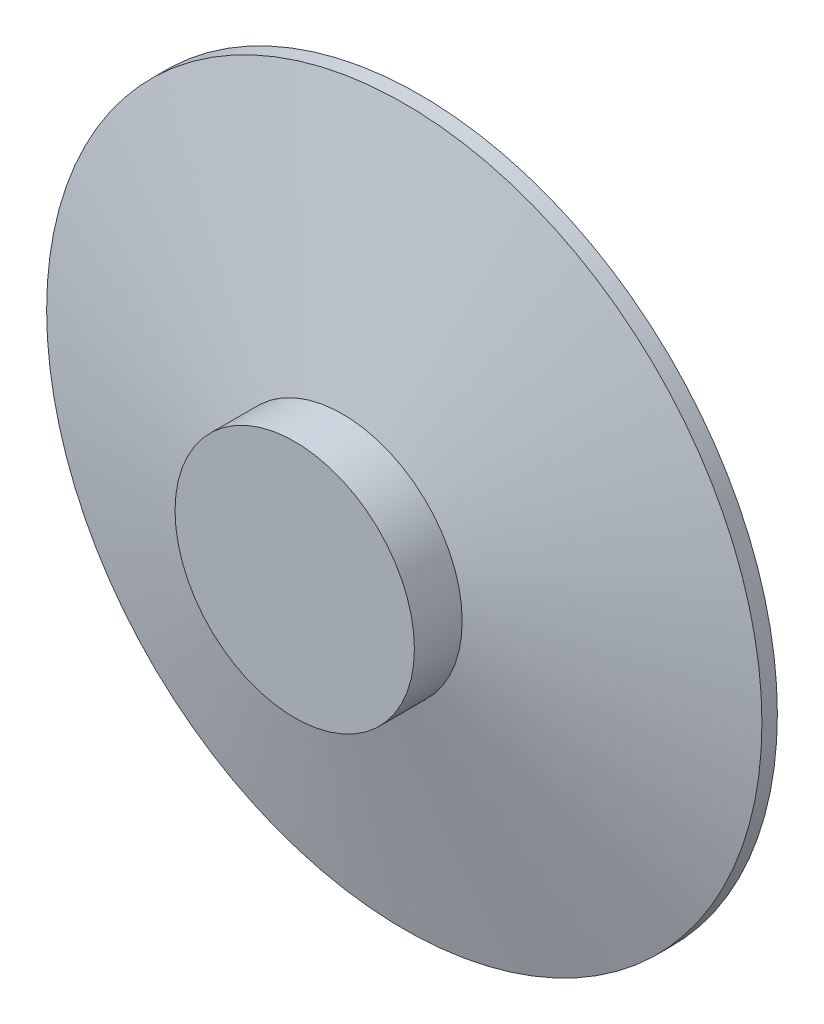
SolidWorks part; units mm, degrees
material "6061-T6 (SS)"
ref_plane "Front" through (0, 0, 0) normal (0, 0, 1) x (1, 0, 0)
ref_plane "Top" through (0, 0, 0) normal (0, 1, 0) x (1, 0, 0)
ref_plane "Right" through (0, 0, 0) normal (1, 0, 0) x (0, 0, -1)
sketch "Sketch1" plane through (0, 0, 0) normal (1, 0, 0) x (0, 0, -1)
  line L0 (0, 0) -> (47.2597, 0) construction
  line L1 (0, 0) -> (0, 5.8274)
  line L2 (0, 5.8274) -> (2.327, 5.8274)
  line L4 (6.0865, 17.4156) -> (6.0865, 16.25)
  line L5 (4.4942, 0) -> (0, 0)
  line L6 (6.0865, 16.25) -> (4.4942, 0)
  line L7 (2.327, 5.8274) -> (5.3346, 17.4156)
  line L8 (5.3346, 17.4156) -> (6.0865, 17.4156)
  dimension "D1" = 32.5
revolve "Revolve1" add sketch "Sketch1" angle 360 about L0
